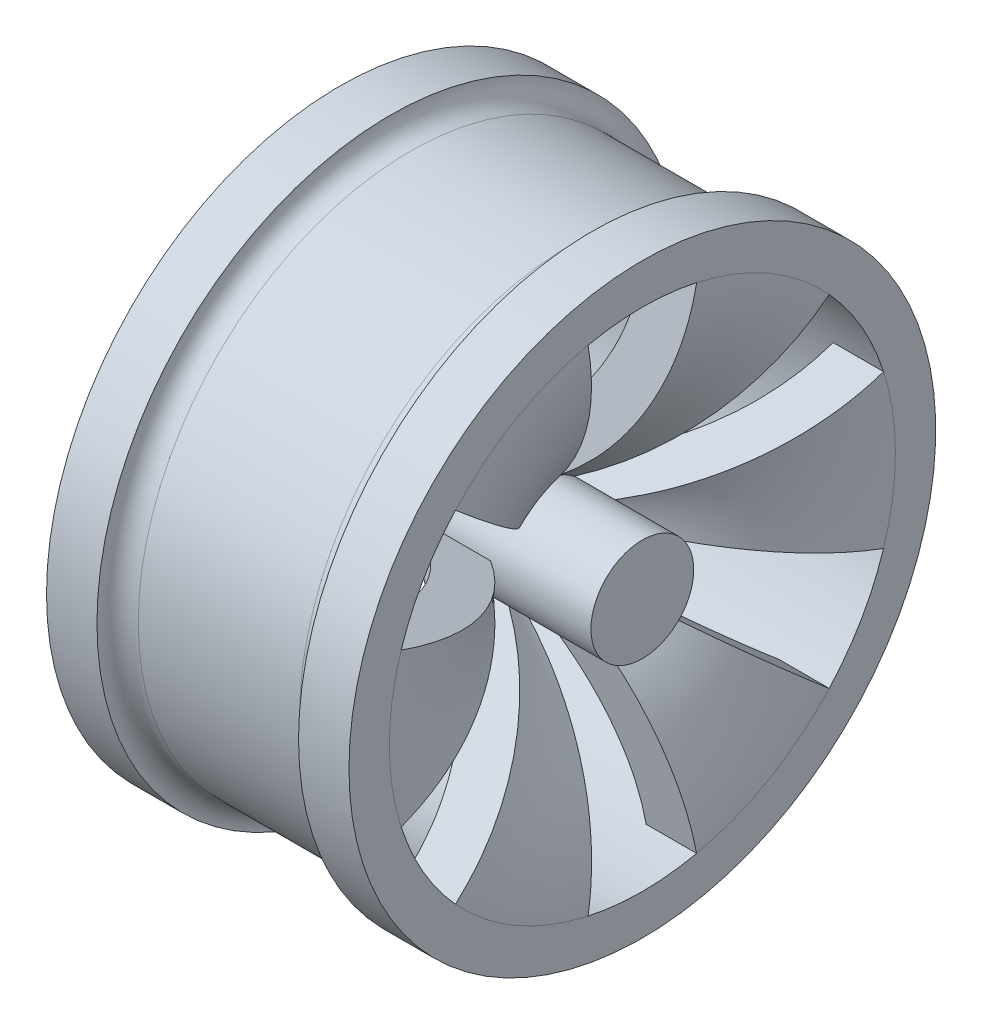
SolidWorks part; units mm, degrees
ref_plane "Alzado" through (0, 0, 0) normal (0, 0, 1) x (1, 0, 0)
ref_plane "Planta" through (0, 0, 0) normal (0, 1, 0) x (1, 0, 0)
ref_plane "Vista lateral" through (0, 0, 0) normal (1, 0, 0) x (0, 0, -1)
sketch "Croquis1" plane through (0, 0, 0) normal (0, 0, 1) x (1, 0, 0)
  line L0 (0, 0) -> (0, 2.1) construction
  line L5 (15, 25.1) -> (15, 29.1)
  line L6 (15, 29.1) -> (9.9975, 29.1)
  line L8 (0, 7.1) -> (0, 27) construction
  line L9 (10, 25.1) -> (-10, 25.1)
  line L11 (8, 27) -> (-8, 27)
  line L12 (-15, 25.1) -> (-15, 29.1)
  line L13 (-15, 29.1) -> (-9.9975, 29.1)
  line L14 (-10, 25.1) -> (-15, 25.1)
  line L17 (0, 2.1) -> (-17, 2.1)
  line L18 (-17, 2.1) -> (-17, 5.1)
  line L20 (-2, 5.1) -> (-17, 5.1)
  line L21 (0, 0) -> (4.0787, 0) construction
  arc A0 (0, 7.1) -> (10, 25.1) centre (-11.2184, 25.1102) ccw
  arc A1 (0, 2.1) -> (15, 25.1) centre (-10.6396, 25.4301) ccw
  arc A2 (8, 27) -> (9.9975, 29.1) centre (8, 29) ccw
  arc A3 (-8, 27) -> (-9.9975, 29.1) centre (-8, 29) cw
  arc A4 (-2, 5.1) -> (0, 7.1) centre (-6.9681, 12.0681) ccw
  point P20 (0, 25.1)
  dimension "D1" = 2.1
  dimension "D2" = 5
  dimension "D3" = 4
  dimension "D4" = 5
revolve "Revolución1" add sketch "Croquis1" angle 360 about L21
sketch "Croquis2" plane through (-15, 0, 0) normal (-1, 0, 0) x (0, 0, 1)
  circle A0 centre (0, 0) radius 2.1 construction
  circle A1 centre (0, 0) radius 2.1
  circle A2 centre (0, 0) radius 5.1 construction
  circle A3 centre (0, 0) radius 5.1
extrude "Saliente-Extruir1" add sketch "Croquis2" against normal blind 30
sketch "Croquis3" plane through (15, 0, 0) normal (1, 0, 0) x (0, 0, -1)
  circle A0 centre (0, 0) radius 5.1 construction
  circle A1 centre (0, 0) radius 5.1
extrude "Saliente-Extruir2" add sketch "Croquis3" against normal blind 5
sketch "Croquis4" plane through (15, 0, 0) normal (1, 0, 0) x (0, 0, -1)
  line L0 (-1.811, 4.7676) -> (-5.3852, 24.5155)
  line L1 (1.8068, 4.7692) -> (5.3852, 24.5155)
  circle A1 centre (0, 0) radius 5.1 construction
  circle A3 centre (0, 0) radius 25.1 construction
  circle A4 centre (0, 0) radius 5.1 construction
  arc A5 (-5.3852, 24.5155) -> (5.3852, 24.5155) centre (0, 0) cw
  arc A6 (-1.811, 4.7676) -> (1.8068, 4.7692) centre (0, 0) cw
  point P6 (0, 0)
  point P11 (0, 0)
extrude "Cortar-Extruir1" cut sketch "Croquis4" against normal blind 17
pattern_circular "MatrizC1" count 6 every 60 about axis through (0, 0, 0) along (1, 0, 0) of "Cortar-Extruir1"
ref_plane "Plano1" through (0, 6, 0) normal (0, 1, 0) x (1, 0, 0)
sketch "Croquis5" plane through (0, 6, 0) normal (0, 1, 0) x (1, 0, 0)
  line L0 (0, 0) -> (-15, 0)
  line L1 (-15, 29.1) -> (-15, -29.1) construction
  circle A0 centre (-15, 0) radius 1.6
  dimension "D1" = 3.2
extrude "Cortar-Extruir2" cut sketch "Croquis5" against normal blind 6 contours A0
